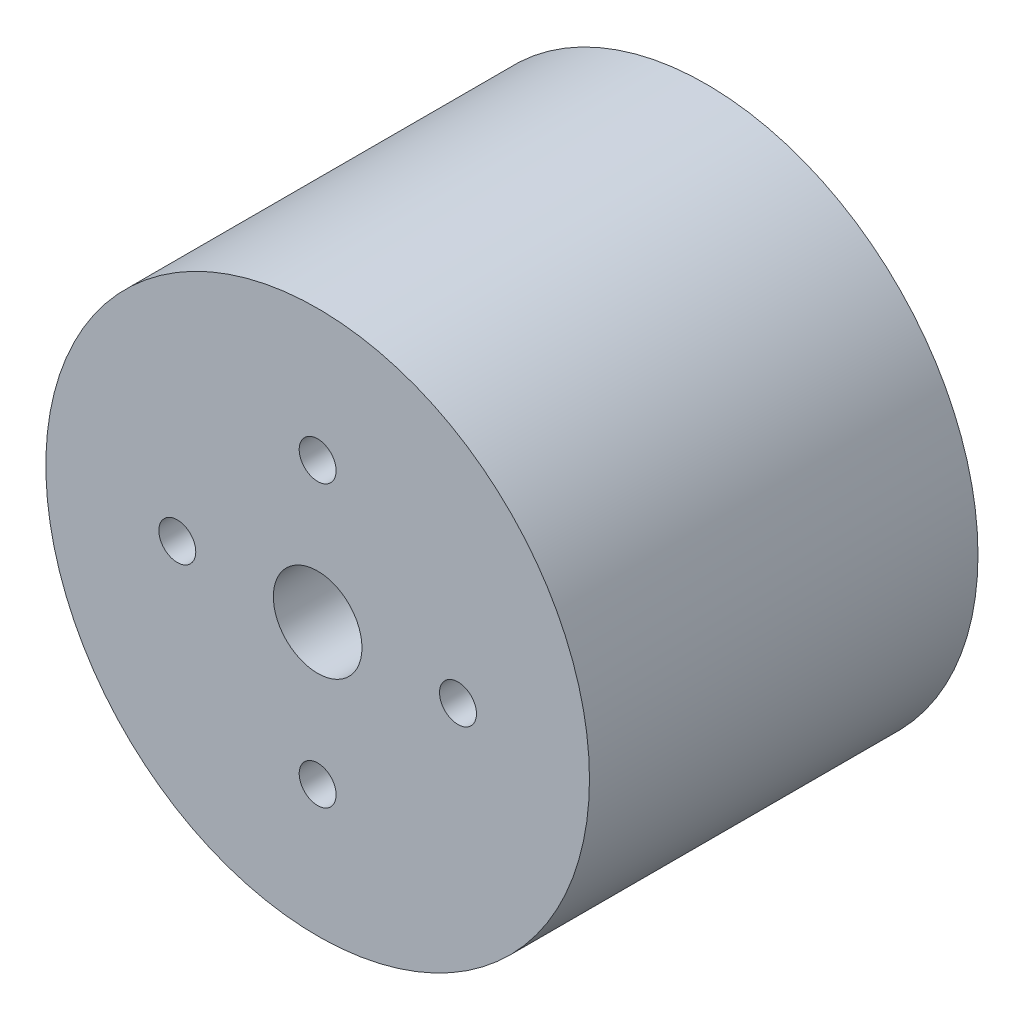
SolidWorks part; units mm, degrees
ref_plane "Alzado" through (0, 0, 0) normal (0, 0, 1) x (1, 0, 0)
ref_plane "Planta" through (0, 0, 0) normal (0, 1, 0) x (1, 0, 0)
ref_plane "Vista lateral" through (0, 0, 0) normal (1, 0, 0) x (0, 0, -1)
sketch "Croquis1" plane through (0, 0, 0) normal (0, 0, 1) x (1, 0, 0)
  circle A0 centre (0, 0) radius 18.4
  dimension "D1" = 36.8
extrude "Saliente-Extruir1" add sketch "Croquis1" along normal blind 26.3
sketch "Croquis2" plane through (0, 0, 26.3) normal (0, 0, 1) x (1, 0, 0)
  circle A0 centre (0, 0) radius 3
  circle A1 centre (0, 0) radius 9.5 construction
  circle A2 centre (0, 9.5) radius 1.25
  circle A3 centre (9.5, 0) radius 1.25
  circle A4 centre (0, -9.5) radius 1.25
  circle A5 centre (-9.5, 0) radius 1.25
  point P15 (0, 0)
  dimension "D1" = 6
  dimension "D2" = 19
  dimension "D3" = 2.5
  dimension "D4" = 4
extrude "Cortar-Extruir1" cut sketch "Croquis2" against normal blind 5
sketch "Croquis3" plane through (0, 0, 0) normal (0, 0, -1) x (-1, 0, 0)
  circle A0 centre (0, 0) radius 10 construction
  circle A1 centre (-10, 0) radius 1.25
  circle A2 centre (0, 10) radius 1.25
  circle A3 centre (10, 0) radius 1.25
  circle A4 centre (0, -10) radius 1.25
  point P14 (0, 0)
  dimension "D1" = 20
  dimension "D2" = 2.5
  dimension "D3" = 4
extrude "Cortar-Extruir2" cut sketch "Croquis3" against normal blind 5
